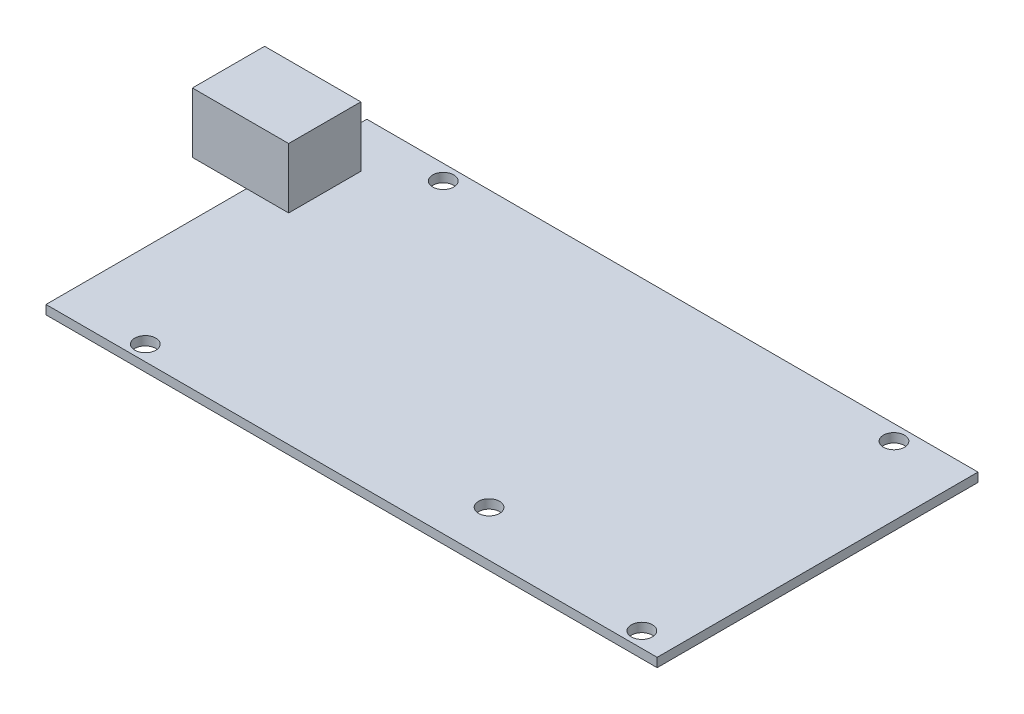
SolidWorks part; units mm, degrees
ref_plane "前视基准面" through (0, 0, 0) normal (0, 0, 1) x (1, 0, 0)
ref_plane "上视基准面" through (0, 0, 0) normal (0, 1, 0) x (1, 0, 0)
ref_plane "右视基准面" through (0, 0, 0) normal (1, 0, 0) x (0, 0, -1)
sketch "草图1" plane through (0, 0, 0) normal (0, 1, 0) x (1, 0, 0)
  line L1 (-35.9937, -21.3215) -> (65.6063, -21.3215)
  line L2 (-35.9937, -21.3215) -> (-35.9937, 32.0185)
  line L3 (-35.9937, 32.0185) -> (65.6063, 32.0185)
  line L4 (65.6063, -21.3215) -> (65.6063, 32.0185)
  dimension "D1" = 53.34
  dimension "D2" = 101.6
extrude "凸台-拉伸1" add sketch "草图1" along normal blind 1.5
sketch "草图2" plane through (0, 1.5, 0) normal (0, 1, 0) x (1, 0, 0)
  line L0 (65.6063, 32.0185) -> (-35.9937, 32.0185) construction
  line L1 (-44.9937, 24.0185) -> (-28.9937, 24.0185)
  line L2 (-44.9937, 24.0185) -> (-44.9937, 12.0185)
  line L3 (-44.9937, 12.0185) -> (-28.9937, 12.0185)
  line L4 (-28.9937, 24.0185) -> (-28.9937, 12.0185)
  line L5 (-35.9937, 32.0185) -> (-35.9937, -21.3215) construction
  dimension "D1" = 8
  dimension "D2" = 12
  dimension "D3" = 16
  dimension "D4" = 7
extrude "凸台-拉伸2" add sketch "草图2" along normal blind 10 contours L2 L1 L4 L3
sketch "草图3" plane through (-44.9937, 0, 0) normal (-1, 0, 0) x (0, 0, 1)
  line L1 (-21.0185, 10.5) -> (-23.0185, 8.5)
  line L2 (-24.0185, 10.5) -> (-12.0185, 10.5)
  line L3 (-21.0185, 10.5) -> (-15.0185, 10.5)
  line L4 (-15.0185, 10.5) -> (-13.0185, 8.5)
  line L5 (-13.0185, 2.5) -> (-24.0185, 2.5)
  line L6 (-13.0185, 11.5) -> (-13.0185, 2.5)
  line L7 (-13.0185, 2.5) -> (-23.0185, 2.5)
  line L8 (-13.0185, 8.5) -> (-13.0185, 2.5)
  line L9 (-23.0185, 11.5) -> (-23.0185, 1.5)
  line L10 (-23.0185, 8.5) -> (-23.0185, 2.5)
  line L12 (-21.0185, 7.5531) -> (-15.0185, 7.5531)
  line L13 (-21.0185, 7.5531) -> (-21.0185, 5.3896)
  line L14 (-21.0185, 5.3896) -> (-15.0185, 5.3896)
  line L15 (-15.0185, 7.5531) -> (-15.0185, 5.3896)
  point P3 (-23.0185, 10.5)
  point P13 (-13.0185, 10.5)
  dimension "D1" = 1
  dimension "D2" = 1
  dimension "D3" = 1
extrude "切除-拉伸1" cut sketch "草图3" against normal blind 10
sketch "草图6" plane through (0, 1.5, 0) normal (0, 1, 0) x (1, 0, 0)
  line L0 (-35.9937, -21.3215) -> (65.6063, -21.3215) construction
  line L1 (-35.9937, 12.0185) -> (-35.9937, -21.3215) construction
  line L2 (-35.9937, 32.0185) -> (-35.9937, 24.0185) construction
  circle A0 centre (-20.7537, 29.4785) radius 1.75
  circle A1 centre (54.1763, 29.4785) radius 1.75
  circle A2 centre (-22.0237, -18.7815) radius 1.75
  circle A3 centre (30.0463, -13.7015) radius 1.75
  circle A4 centre (60.5263, -18.7815) radius 1.75
  dimension "D1" = 50.8
  dimension "D2" = 2.54
  dimension "D3" = 13.97
  dimension "D4" = 66.04
  dimension "D5" = 96.52
  dimension "D6" = 2.54
  dimension "D7" = 7.62
  dimension "D8" = 15.24
  dimension "D9" = 90.17
  dimension "D10" = 50.8
extrude "切除-拉伸2" cut sketch "草图6" against normal through all
